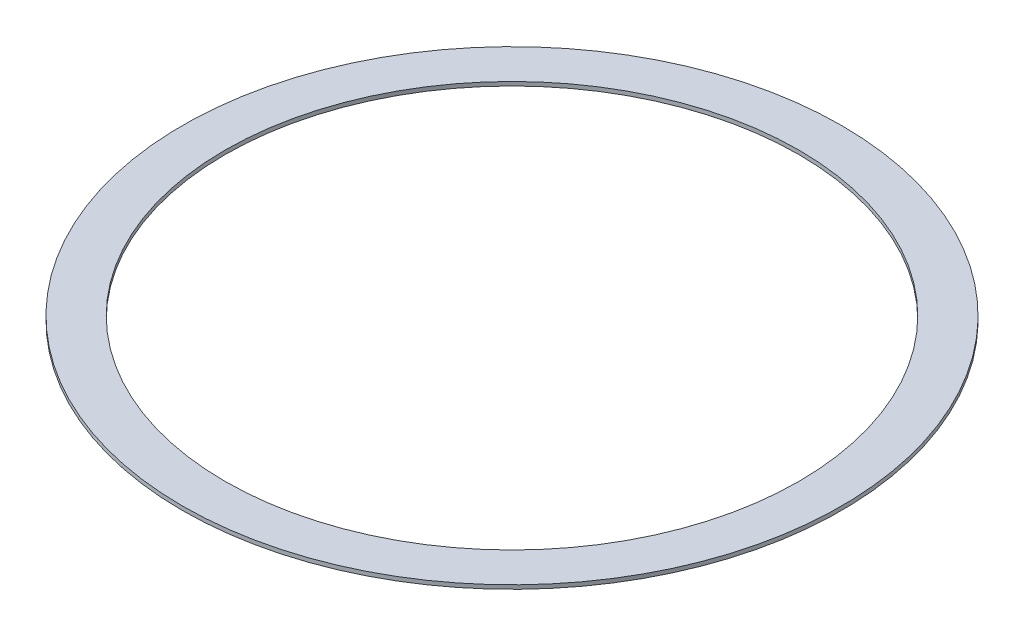
SolidWorks part; units mm, degrees
ref_plane "Front Plane" through (0, 0, 0) normal (0, 0, 1) x (1, 0, 0)
ref_plane "Top Plane" through (0, 0, 0) normal (0, 1, 0) x (1, 0, 0)
ref_plane "Right Plane" through (0, 0, 0) normal (1, 0, 0) x (0, 0, -1)
sketch "Sketch1" plane through (0, 0, 0) normal (0, 1, 0) x (1, 0, 0)
  circle A1 centre (0, 0) radius 55.5625
  circle A2 centre (0, 0) radius 63.8175
  dimension "D1" = 111.125
  dimension "D2" = 8.255
extrude "Boss-Extrude2" add sketch "Sketch1" along normal blind 0.762 contours A2 A1
equation "\"Middle Coupler Inner Daimeter\"= 3.875in"
equation "\"Middle Coupler  Wall Thickness\" = 0.25in"
equation "\"Middle Coupler Bottom Thickness\"= 0.2in"
equation "\"Bearing Rail Offset\"= 0.45in"
equation "\"3-56 UNF Tap\"= 0.089in"
equation "\"3-48 Tap\"= 0.079in"
equation "\"3-56 UNF Clearance\"= 0.104in"
equation "\"3-48 Clearance\" = 0.104in"
equation "\"Ball Bearing Distance\"= 0.03in"
equation "\"TCA Outer Diameter\" = 6in"
equation "\"Interstage Aeroframe Wall Thickness\" = 0.072in"
equation "\"Compression Spring OD\"= 0.42in"
equation "\"10-24 Tap\"= 0.157in"
equation "\"10-24 Clearance\"= 0.196in"
equation "\"Lower Stage Fuselage Wall Thickness\" = 0.25in"
equation "\"6-32 Tap\" = 0.107in"
equation "\"6-32 Clearance\" = 0.144"
equation "\"1/4-20 Tap\" = 0.201in"
equation "\"12-24 Tap\" = 0.177in"
equation "\"D1@Sketch1\"=\"Middle Coupler Inner Daimeter\" + 2*\"Middle Coupler  Wall Thickness\""
equation "\"D2@Sketch1\"=0.575 - \"Middle Coupler  Wall Thickness\""
